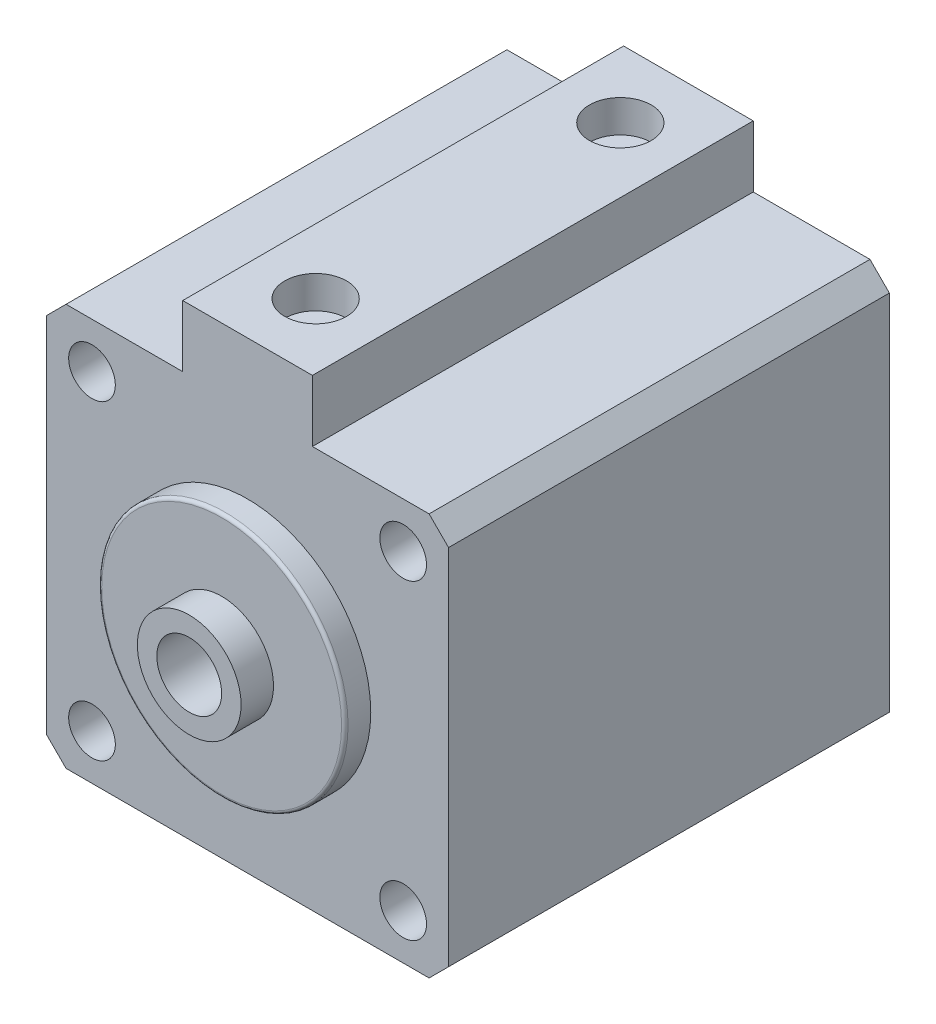
SolidWorks part; units mm, degrees
ref_plane "Front" through (0, 0, 0) normal (0, 0, 1) x (1, 0, 0)
ref_plane "Top" through (0, 0, 0) normal (0, 1, 0) x (1, 0, 0)
ref_plane "Right" through (0, 0, 0) normal (1, 0, 0) x (0, 0, -1)
sketch "Esquisse1" plane through (0, 0, 0) normal (0, 0, 1) x (1, 0, 0)
  line L1 (0, 0) -> (62, 0)
  line L2 (0, 0) -> (0, 62)
  line L3 (0, 62) -> (62, 62)
  line L4 (62, 0) -> (62, 62)
  dimension "D1" = 62
  dimension "D2" = 62
extrude "Boss.-Extru.1" add sketch "Esquisse1" along normal blind 68
sketch "Esquisse2" plane through (0, 0, 68) normal (0, 0, 1) x (1, 0, 0)
  line L0 (62, 31) -> (0, 31) construction
  line L1 (62, 0) -> (62, 62) construction
  line L2 (0, 62) -> (0, 0) construction
  circle A0 centre (31, 31) radius 19
  dimension "D1" = 38
extrude "Boss.-Extru.2" add sketch "Esquisse2" along normal blind 4
sketch "Esquisse3" plane through (0, 0, 72) normal (0, 0, 1) x (1, 0, 0)
  circle A0 centre (31, 31) radius 8
  dimension "D1" = 16
extrude "Boss.-Extru.3" add sketch "Esquisse3" along normal blind 5
sketch "Esquisse4" plane through (0, 0, 68) normal (0, 0, 1) x (1, 0, 0)
  line L0 (31, 62) -> (31, 31) construction
  line L1 (62, 62) -> (0, 62) construction
  line L2 (31, 31) -> (0, 31) construction
  line L3 (0, 62) -> (0, 0) construction
  circle A0 centre (7, 55) radius 3.6
  circle A1 centre (55, 55) radius 3.6
  circle A2 centre (55, 7) radius 3.6
  circle A3 centre (7, 7) radius 3.6
  dimension "D1" = 48
  dimension "D2" = 48
  dimension "D3" = 7.2
extrude "Enlèv. mat.-Extru.1" cut sketch "Esquisse4" against normal through all both and the other way through all
chamfer "Chanfrein1" distance 3 angle 45 4 edges at (62, 62, 34) (62, 0, 34) (0, 0, 34) (0, 62, 34)
sketch "Esquisse5" plane through (0, 0, 68) normal (0, 0, 1) x (1, 0, 0)
  line L0 (59, 62) -> (3, 62) construction
  line L1 (21, 62) -> (41, 62)
  line L2 (21, 62) -> (21, 71.5)
  line L3 (21, 71.5) -> (41, 71.5)
  line L4 (41, 62) -> (41, 71.5)
  line L5 (31, 71.5) -> (31, 62) construction
  line L6 (3, 0) -> (59, 0) construction
  dimension "D1" = 71.5
  dimension "D2" = 20
extrude "Boss.-Extru.4" add sketch "Esquisse5" against normal up to vertex (68 mm away) up to point (59, 62, 0)
sketch "Esquisse6" plane through (0, 71.5, 0) normal (0, 1, 0) x (1, 0, 0)
  line L0 (31, -68) -> (31, 0) construction
  line L1 (41, -68) -> (21, -68) construction
  line L2 (41, 0) -> (21, 0) construction
  line L3 (31, -34) -> (21, -34) construction
  line L4 (21, 0) -> (21, -68) construction
  circle A0 centre (31, -57.5) radius 4.7625
  circle A1 centre (31, -10.5) radius 4.7625
  dimension "D1" = 10.5
  dimension "D2" = 9.525
extrude "Enlèv. mat.-Extru.2" cut sketch "Esquisse6" against normal blind 5
sketch "Esquisse7" plane through (0, 0, 77) normal (0, 0, 1) x (1, 0, 0)
  circle A0 centre (31, 31) radius 5
  dimension "D1" = 10
extrude "Enlèv. mat.-Extru.3" cut sketch "Esquisse7" against normal blind 70
fillet "Congé1" radius 0.5 1 edges at (50, 31, 72)
